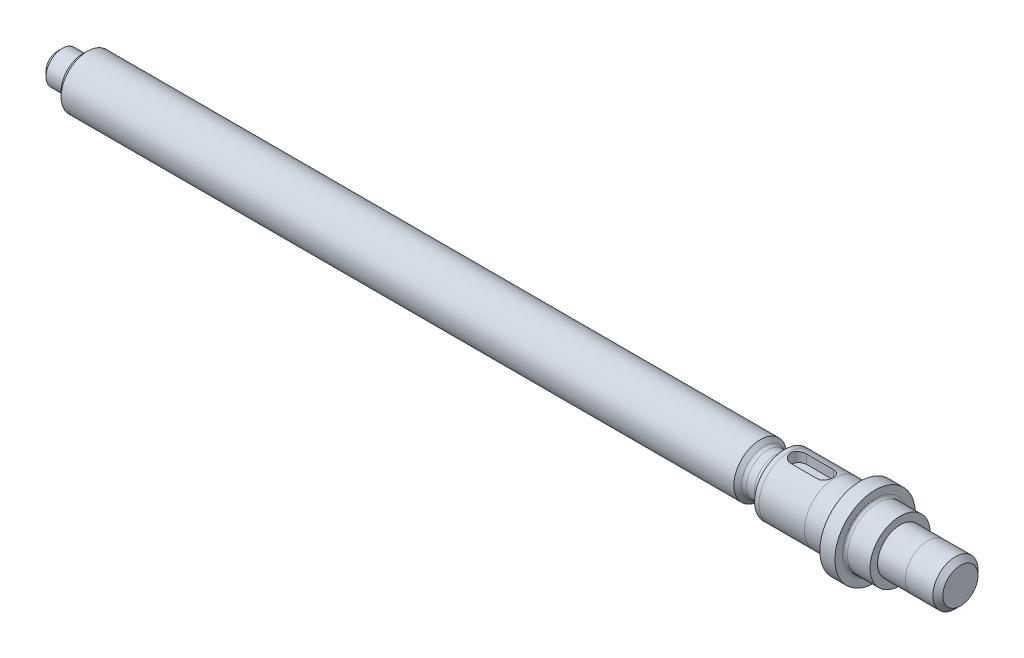
SolidWorks part; units mm, degrees
ref_plane "Спереди" through (0, 0, 0) normal (0, 0, 1) x (1, 0, 0)
ref_plane "Сверху" through (0, 0, 0) normal (0, 1, 0) x (1, 0, 0)
ref_plane "Справа" through (0, 0, 0) normal (1, 0, 0) x (0, 0, -1)
sketch "Эскиз1" plane through (0, 0, 0) normal (0, 1, 0) x (1, 0, 0)
  line L0 (55.7564, -2.4973) -> (55.7564, -6.9973)
  line L1 (55.7564, -6.9973) -> (43.7564, -6.9973)
  line L2 (43.7564, -6.9973) -> (43.7564, -8.4973)
  line L3 (43.7564, -8.4973) -> (38.7564, -8.4973)
  line L4 (38.7564, -8.4973) -> (38.7564, -10.4973)
  line L5 (38.7564, -10.4973) -> (35.7564, -10.4973)
  line L6 (35.7564, -10.4973) -> (35.7564, -8.4973)
  line L7 (35.7564, -8.4973) -> (20.7564, -8.4973)
  line L8 (18.9564, -6.6973) -> (16.9564, -6.6973)
  line L9 (16.9564, -6.6973) -> (15.8958, -7.7579)
  line L10 (15.8958, -7.7579) -> (-119.0894, -7.7579)
  line L11 (-119.0894, -7.7579) -> (-119.0894, -5.7579)
  line L12 (-119.0894, -5.7579) -> (-124.0894, -5.7579)
  line L13 (-124.0894, -5.7579) -> (-124.0894, -2.4973)
  line L14 (-124.0894, -2.1474) -> (-124.0894, -2.4973) construction
  line L15 (-124.0894, -2.4973) -> (55.7564, -2.4973) construction
  line L16 (55.7564, -2.4973) -> (-124.0894, -2.4973)
  arc A0 (20.7564, -8.4973) -> (18.9564, -6.6973) centre (18.9564, -8.4973) ccw
  dimension "D1" = 4.5
  dimension "D2" = 3.2607
revolve "Повернуть1" add sketch "Эскиз1" angle 360 about L16
fillet "Скругление1" radius 0.5 1 edges at (35.7564, 0, -3.5027)
fillet "Скругление2" radius 0.5 1 edges at (38.7564, 0, -3.5027)
fillet "Скругление3" radius 1 1 edges at (16.9564, 0, -1.7027)
fillet "Скругление4" radius 0.5 1 edges at (-119.0894, 0, -0.7634)
chamfer "Фаска1" distance 1 angle 45 2 edges at (55.7564, 0, -2.0027) (-119.0894, 0, -2.7634)
chamfer "Фаска2" distance 1 angle 45 1 edges at (-124.0894, 0, -0.7634)
ref_plane "Плоскость1" through (0, 10, 0) normal (0, 1, 0) x (1, 0, 0)
sketch "Эскиз2" plane through (0, 10, 0) normal (0, 1, 0) x (1, 0, 0)
  line L0 (23.5509, -2.4973) -> (28.8684, -2.4973) construction
  line L1 (23.5509, -0.9029) -> (28.8684, -0.9029)
  line L2 (23.5509, -4.0917) -> (28.8684, -4.0917)
  arc A0 (23.5509, -0.9029) -> (23.5509, -4.0917) centre (23.5509, -2.4973) ccw
  arc A1 (28.8684, -4.0917) -> (28.8684, -0.9029) centre (28.8684, -2.4973) ccw
  point P2 (26.2096, -2.4973)
extrude "Вырез-Вытянуть1" cut sketch "Эскиз2" against normal blind 6
sketch "Эскиз3" plane through (0, 10, 0) normal (0, 1, 0) x (1, 0, 0)
  line L0 (30.681, -10.4132) -> (30.681, 4.2474)
  line L1 (21.6418, -9.6937) -> (21.6418, 6.361)
split line "Разделяющая линия4"
sketch "Эскиз4" plane through (0, 10, 0) normal (0, 1, 0) x (1, 0, 0)
  line L0 (49.2564, 2.0027) -> (49.2564, -6.9973)
  line L1 (54.7564, 2.0027) -> (43.7564, 2.0027) construction
  line L2 (43.7564, -6.9973) -> (54.7564, -6.9973) construction
split line "Разделяющая линия5"
